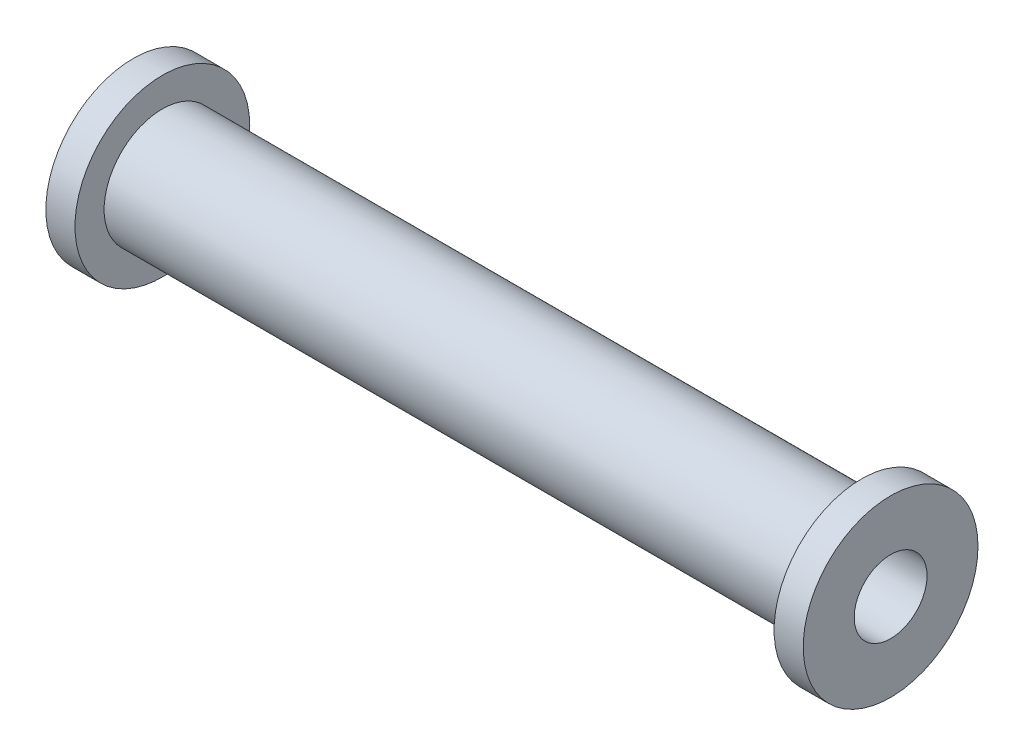
SolidWorks part; units mm, degrees
ref_plane "Front Plane" through (0, 0, 0) normal (0, 0, 1) x (1, 0, 0)
ref_plane "Top Plane" through (0, 0, 0) normal (0, 1, 0) x (1, 0, 0)
ref_plane "Right Plane" through (0, 0, 0) normal (1, 0, 0) x (0, 0, -1)
sketch "Sketch1" plane through (0, 0, 0) normal (1, 0, 0) x (0, 0, -1)
  circle A0 centre (0, 0) radius 3
  circle A1 centre (0, 0) radius 1.25
extrude "Boss-Extrude2" add sketch "Sketch1" along normal blind 1
sketch "Sketch2" plane through (1, 0, 0) normal (1, 0, 0) x (0, 0, -1)
  circle A0 centre (0, 0) radius 2
  circle A1 centre (0, 0) radius 1.25
extrude "Boss-Extrude3" add sketch "Sketch2" along normal blind 24
sketch "Sketch3" plane through (25, 0, 0) normal (1, 0, 0) x (0, 0, -1)
  circle A0 centre (0, 0) radius 3
  circle A1 centre (0, 0) radius 1.25
extrude "Boss-Extrude4" add sketch "Sketch3" along normal blind 1
